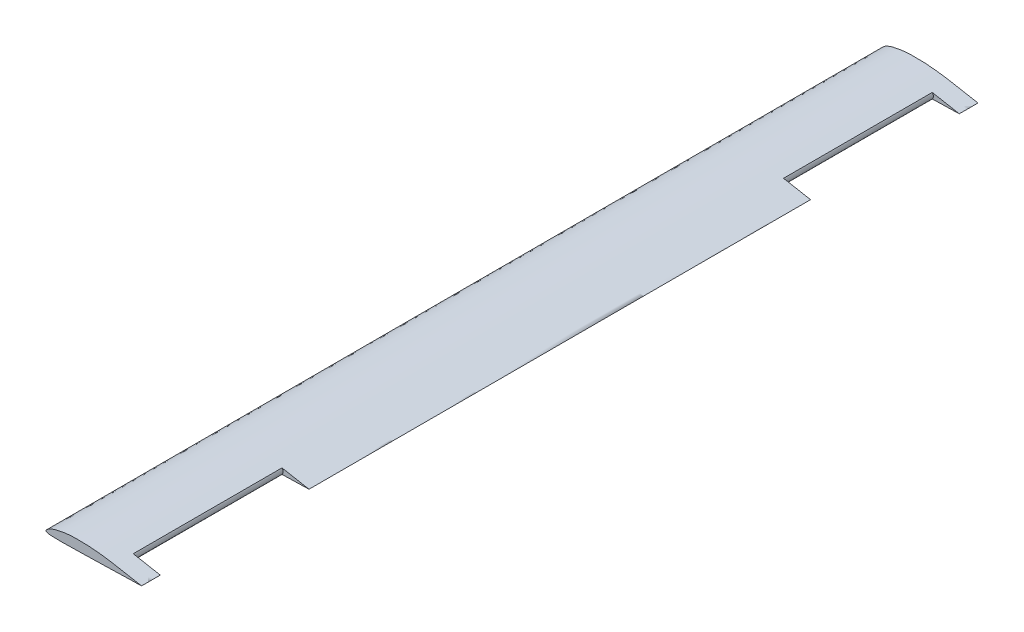
SolidWorks part; units mm, degrees
ref_plane "Front Plane" through (0, 0, 0) normal (0, 0, 1) x (1, 0, 0)
ref_plane "Top Plane" through (0, 0, 0) normal (0, 1, 0) x (1, 0, 0)
ref_plane "Right Plane" through (0, 0, 0) normal (1, 0, 0) x (0, 0, -1)
curve "Curve1"
  spline degree 3 poles (0.9958, -0.0002, 0) (1.001, 0, 0) (0.9959, 0.0004, 0) (0.9918, 0.0012, 0) (0.9819, 0.0027, 0) (0.9699, 0.0048, 0) (0.9542, 0.0075, 0) (0.9358, 0.0109, 0) (0.9145, 0.0148, 0) (0.8908, 0.0194, 0) (0.8648, 0.0244, 0) (0.8367, 0.0299, 0) (0.8069, 0.0358, 0) (0.7756, 0.0418, 0) (0.743, 0.0478, 0) (0.7093, 0.0536, 0) (0.6746, 0.0593, 0) (0.6392, 0.0646, 0) (0.6032, 0.0696, 0) (0.5669, 0.0741, 0) (0.5303, 0.078, 0) (0.4938, 0.0814, 0) (0.4575, 0.084, 0) (0.4216, 0.0859, 0) (0.3863, 0.0872, 0) (0.3516, 0.0876, 0) (0.3179, 0.0873, 0) (0.2852, 0.0862, 0) (0.2537, 0.0842, 0) (0.2236, 0.0815, 0) (0.1949, 0.0781, 0) (0.1678, 0.0739, 0) (0.1424, 0.0692, 0) (0.1188, 0.0638, 0) (0.0972, 0.0579, 0) (0.0776, 0.0516, 0) (0.06, 0.0449, 0) (0.0446, 0.0381, 0) (0.0314, 0.031, 0) (0.0205, 0.024, 0) (0.0118, 0.0172, 0) (0.0054, 0.0106, 0) (0.0016, 0.0048, 0) (-0.0007, -0.0008, 0) (0.0024, -0.0058, 0) (0.0082, -0.0092, 0) (0.0167, -0.0124, 0) (0.0282, -0.0147, 0) (0.0427, -0.0164, 0) (0.0603, -0.0177, 0) (0.0809, -0.0188, 0) (0.1042, -0.0194, 0) (0.1302, -0.02, 0) (0.1586, -0.0201, 0) (0.1892, -0.0202, 0) (0.2219, -0.0198, 0) (0.2565, -0.0194, 0) (0.2927, -0.0185, 0) (0.3303, -0.0176, 0) (0.3692, -0.0166, 0) (0.409, -0.0155, 0) (0.4494, -0.0144, 0) (0.4902, -0.0134, 0) (0.5311, -0.0123, 0) (0.5717, -0.0112, 0) (0.6119, -0.0103, 0) (0.6513, -0.0091, 0) (0.6897, -0.0081, 0) (0.7268, -0.0073, 0) (0.7624, -0.0062, 0) (0.7961, -0.0053, 0) (0.8277, -0.0045, 0) (0.8573, -0.0037, 0) (0.8847, -0.003, 0) (0.9098, -0.0024, 0) (0.9323, -0.0019, 0) (0.9518, -0.0012, 0) (0.9685, -0.0008, 0) (0.9812, -0.0006, 0) (0.9916, -0.0002, 0) (0.9958, -0.0002, 0) (1.001, 0, 0) (0.9959, 0.0004, 0) knots -0.008528 -0.003816 -0.00096 0 0.000951 0.003757 0.008317 0.014522 0.022293 0.03156 0.042221 0.054151 0.067231 0.081331 0.096307 0.112012 0.128327 0.145184 0.162488 0.180136 0.198033 0.216059 0.234134 0.252192 0.270104 0.287817 0.305235 0.322284 0.338896 0.354986 0.370506 0.385417 0.399632 0.413116 0.425823 0.437704 0.448737 0.45888 0.468105 0.476405 0.483748 0.490134 0.495557 0.500012 0.503516 0.506001 0.508215 0.511494 0.515844 0.521547 0.528755 0.537449 0.547575 0.559074 0.571867 0.585873 0.60098 0.61708 0.634081 0.651921 0.670484 0.689642 0.709259 0.729201 0.749303 0.769441 0.789466 0.809254 0.82867 0.847598 0.865915 0.883467 0.900079 0.915618 0.930135 0.943663 0.95605 0.967159 0.976853 0.984996 0.991472 0.996184 0.99904 1 1.000951 1.003757 1.008317 periodic
sketch "Sketch1" plane through (0, 0, 0) normal (0, 0, 1) x (1, 0, 0)
  spline S1 degree 3 poles (149.1678, -0.0309) (150.2077, -0.0064) (149.1856, 0.0796) (148.3623, 0.2385) (146.3836, 0.5358) (143.9755, 0.9628) (140.8452, 1.5091) (137.1575, 2.176) (132.9076, 2.9693) (128.1564, 3.874) (122.95, 4.8879) (117.3393, 5.9846) (111.3795, 7.1508) (105.1224, 8.3627) (98.6041, 9.5664) (91.8579, 10.7273) (84.9242, 11.8625) (77.8367, 12.9284) (70.6388, 13.9152) (63.3717, 14.8201) (56.0682, 15.5996) (48.7695, 16.2706) (41.5085, 16.8046) (34.325, 17.1876) (27.2525, 17.4374) (20.3254, 17.5241) (13.5782, 17.4537) (7.0418, 17.2312) (0.7441, 16.8428) (-5.2871, 16.3024) (-11.0261, 15.6192) (-16.4429, 14.786) (-21.519, 13.8367) (-26.2304, 12.7634) (-30.5573, 11.5855) (-34.484, 10.3237) (-37.9928, 8.9896) (-41.0735, 7.6116) (-43.713, 6.2077) (-45.9013, 4.7987) (-47.6312, 3.4329) (-48.9187, 2.1223) (-49.6801, 0.9599) (-50.1484, -0.1551) (-49.5243, -1.167) (-48.3626, -1.8422) (-46.665, -2.4855) (-44.3631, -2.9499) (-41.4511, -3.2787) (-37.931, -3.5468) (-33.8249, -3.7681) (-29.1585, -3.888) (-23.9658, -3.9969) (-18.2827, -4.0237) (-12.1512, -4.0325) (-5.6138, -3.9608) (1.2939, -3.8709) (8.5341, -3.6968) (16.0669, -3.521) (23.8402, -3.3213) (31.8, -3.0988) (39.8876, -2.8724) (48.047, -2.6865) (56.2167, -2.4608) (64.3437, -2.2341) (72.3738, -2.0501) (80.2537, -1.8173) (87.9351, -1.6172) (95.3645, -1.4519) (102.4785, -1.2397) (109.2165, -1.0613) (115.5436, -0.9076) (121.4518, -0.7409) (126.9334, -0.6016) (131.952, -0.4863) (136.4547, -0.3711) (140.3684, -0.2405) (143.6923, -0.1607) (146.2403, -0.1176) (148.3132, -0.0351) (149.1678, -0.0309) (150.2077, -0.0064) (149.1856, 0.0796) knots -0.008528 -0.003816 -0.00096 0 0.000951 0.003757 0.008317 0.014522 0.022293 0.03156 0.042221 0.054151 0.067231 0.081331 0.096307 0.112012 0.128327 0.145184 0.162488 0.180136 0.198033 0.216059 0.234134 0.252192 0.270104 0.287817 0.305235 0.322284 0.338896 0.354986 0.370506 0.385417 0.399632 0.413116 0.425823 0.437704 0.448737 0.45888 0.468105 0.476405 0.483748 0.490134 0.495557 0.500012 0.503516 0.506001 0.508215 0.511494 0.515844 0.521547 0.528755 0.537449 0.547575 0.559074 0.571867 0.585873 0.60098 0.61708 0.634081 0.651921 0.670484 0.689642 0.709259 0.729201 0.749303 0.769441 0.789466 0.809254 0.82867 0.847598 0.865915 0.883467 0.900079 0.915618 0.930135 0.943663 0.95605 0.967159 0.976853 0.984996 0.991472 0.996184 0.99904 1 1.000951 1.003757 1.008317 only from (150, 0) to (150, 0)
  dimension "D1" = 150
extrude "Boss-Extrude1" add sketch "Sketch1" along normal mid plane 1750 contours S1
sketch "Sketch2" plane through (0, 0, 0) normal (0, 1, 0) x (1, 0, 0)
  line L1 (-40.3803, -54.2778) -> (40.3803, -54.2778)
  line L2 (-40.3803, -54.2778) -> (-40.3803, 54.2778)
  line L3 (-40.3803, 54.2778) -> (40.3803, 54.2778)
  line L4 (40.3803, -54.2778) -> (40.3803, 54.2778)
  line L5 (-40.3803, -54.2778) -> (40.3803, 54.2778) construction
  line L6 (-40.3803, 54.2778) -> (40.3803, -54.2778) construction
  point P0 (0, 0)
extrude "Boss-Extrude2" add sketch "Sketch2" against normal blind 10
sketch "Sketch3" plane through (0, 0, 0) normal (0, 1, 0) x (1, 0, 0)
  line L0 (0, 0) -> (0, 400) construction
  line L2 (-37.2811, 378.2619) -> (37.2811, 378.2619)
  line L3 (-37.2811, 378.2619) -> (-37.2811, 421.7381)
  line L4 (-37.2811, 421.7381) -> (37.2811, 421.7381)
  line L5 (37.2811, 378.2619) -> (37.2811, 421.7381)
  line L6 (-37.2811, 378.2619) -> (37.2811, 421.7381) construction
  line L7 (-37.2811, 421.7381) -> (37.2811, 378.2619) construction
  dimension "D1" = 400
extrude "Boss-Extrude3" add sketch "Sketch3" against normal blind 10
mirror "Mirror1" about plane through (0, 0, 0) normal (0, 0, 1) of "Boss-Extrude3"
sketch "Sketch4" plane through (0, 0, 0) normal (0, 1, 0) x (1, 0, 0)
  line L0 (150, -875) -> (150, 875) construction
  line L1 (150, 835.8776) -> (93.4519, 835.8776)
  line L2 (150, 835.8776) -> (150, 524.6851)
  line L3 (150, 524.6851) -> (93.4519, 524.6851)
  line L4 (93.4519, 835.8776) -> (93.4519, 524.6851)
extrude "Cut-Extrude1" cut sketch "Sketch4" against normal through all both and the other way through all
mirror "Mirror2" about plane through (0, 0, 0) normal (0, 0, 1) of "Cut-Extrude1"
sketch "Sketch5" plane through (0, 0, 524.6851) normal (0, 0, 1) x (1, 0, 0)
  line L0 (93.4519, 10.4485) -> (93.4519, -1.4908)
  arc A0 (93.4519, 10.4485) -> (93.4519, -1.4908) centre (87.4822, 4.4789) cw
extrude "Boss-Extrude4" add sketch "Sketch5" along normal up to surface (311.1925 mm away) up to face at (93.4519, 7.4637, 835.8776)
sketch "Sketch6" plane through (0, 0, -835.8776) normal (0, 0, 1) x (1, 0, 0)
  line L0 (93.4519, 10.4485) -> (93.4519, -1.4908)
  arc A0 (93.4519, 10.4485) -> (93.4519, -1.4908) centre (87.4822, 4.4789) cw
extrude "Boss-Extrude5" add sketch "Sketch6" along normal up to surface (311.1925 mm away) up to face at (93.4519, 1.494, -524.6851)
